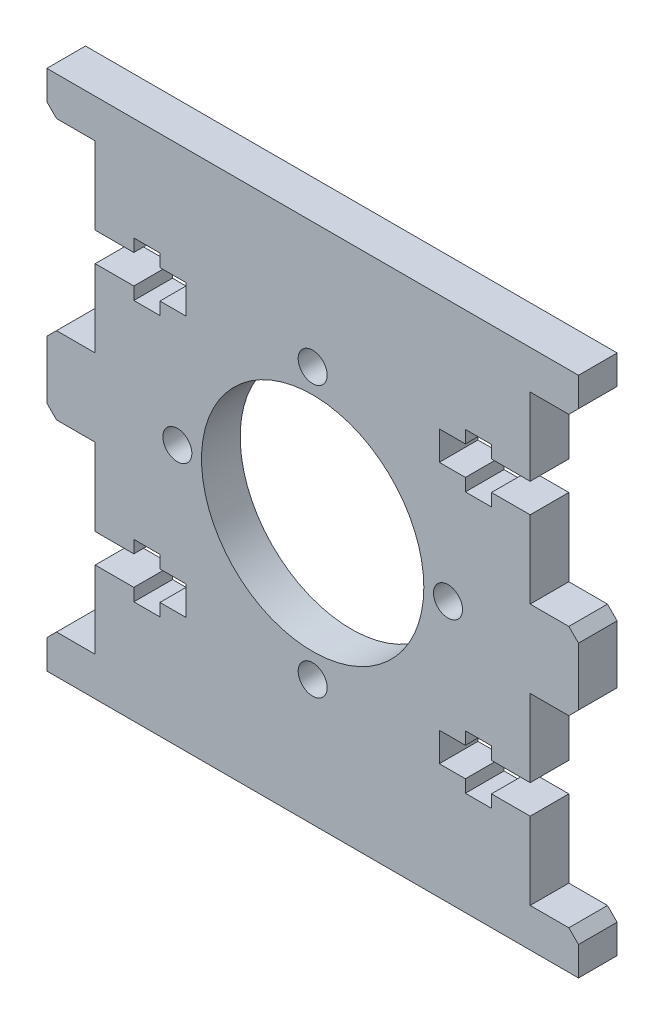
SolidWorks part; units mm, degrees
ref_plane "前视基准面" through (0, 0, 0) normal (0, 0, 1) x (1, 0, 0)
ref_plane "上视基准面" through (0, 0, 0) normal (0, 1, 0) x (1, 0, 0)
ref_plane "右视基准面" through (0, 0, 0) normal (1, 0, 0) x (0, 0, -1)
sketch "草图1" plane through (0, 0, 0) normal (0, 0, 1) x (1, 0, 0)
  line L0 (-22.5, 0) -> (-24.9483, 0) construction
  line L1 (22.5, -27) -> (-22.5, -27)
  line L3 (22.5, 27) -> (-22.5, 27)
  line L4 (-22.5, -27) -> (-22.5, 27) construction
  line L5 (22.5, -27) -> (-22.5, 27) construction
  line L6 (22.5, 27) -> (-22.5, -27) construction
  line L7 (-22.5, 4) -> (-27.5, 4)
  line L8 (-27.5, 4) -> (-27.5, -4)
  line L9 (-27.5, -4) -> (-22.5, -4)
  line L10 (-22.5, 15) -> (-18.5, 15)
  line L11 (-18.5, 15) -> (-18.5, 16.3)
  line L12 (-18.5, 16.3) -> (-15.8, 16.3)
  line L13 (-15.8, 16.3) -> (-15.8, 15)
  line L14 (-15.8, 15) -> (-13.1, 15)
  line L15 (-13.1, 15) -> (-13.1, 12)
  line L16 (-13.1, 12) -> (-15.8, 12)
  line L17 (-15.8, 12) -> (-15.8, 10.7)
  line L18 (-15.8, 10.7) -> (-18.5, 10.7)
  line L19 (-18.5, 10.7) -> (-18.5, 12)
  line L20 (-18.5, 12) -> (-22.5, 12)
  line L21 (-18.5, -12) -> (-22.5, -12)
  line L22 (-18.5, -10.7) -> (-18.5, -12)
  line L23 (-15.8, -10.7) -> (-18.5, -10.7)
  line L24 (-15.8, -12) -> (-15.8, -10.7)
  line L25 (-13.1, -12) -> (-15.8, -12)
  line L26 (-13.1, -15) -> (-13.1, -12)
  line L27 (-15.8, -15) -> (-13.1, -15)
  line L28 (-15.8, -16.3) -> (-15.8, -15)
  line L29 (-18.5, -16.3) -> (-15.8, -16.3)
  line L30 (-18.5, -15) -> (-18.5, -16.3)
  line L31 (-22.5, -15) -> (-18.5, -15)
  line L32 (-22.5, -23) -> (-27.5, -23)
  line L33 (-27.5, -23) -> (-27.5, -27)
  line L34 (-27.5, -27) -> (-22.5, -27)
  line L35 (-27.5, 23) -> (-27.5, 27)
  line L36 (-22.5, 23) -> (-27.5, 23)
  line L37 (-27.5, 27) -> (-22.5, 27)
  line L38 (0, 0) -> (0, -4) construction
  line L39 (22.5, -27) -> (22.5, 27) construction
  line L40 (22.5, 0) -> (24.9483, 0) construction
  line L41 (27.5, 27) -> (22.5, 27)
  line L42 (22.5, 23) -> (27.5, 23)
  line L43 (27.5, 23) -> (27.5, 27)
  line L44 (27.5, -27) -> (22.5, -27)
  line L45 (27.5, -23) -> (27.5, -27)
  line L46 (22.5, -23) -> (27.5, -23)
  line L47 (22.5, -15) -> (18.5, -15)
  line L48 (18.5, -15) -> (18.5, -16.3)
  line L49 (18.5, -16.3) -> (15.8, -16.3)
  line L50 (15.8, -16.3) -> (15.8, -15)
  line L51 (15.8, -15) -> (13.1, -15)
  line L52 (13.1, -15) -> (13.1, -12)
  line L53 (13.1, -12) -> (15.8, -12)
  line L54 (15.8, -12) -> (15.8, -10.7)
  line L55 (15.8, -10.7) -> (18.5, -10.7)
  line L56 (18.5, -10.7) -> (18.5, -12)
  line L57 (18.5, -12) -> (22.5, -12)
  line L58 (18.5, 12) -> (22.5, 12)
  line L59 (18.5, 10.7) -> (18.5, 12)
  line L60 (15.8, 10.7) -> (18.5, 10.7)
  line L61 (15.8, 12) -> (15.8, 10.7)
  line L62 (13.1, 12) -> (15.8, 12)
  line L63 (13.1, 15) -> (13.1, 12)
  line L64 (15.8, 15) -> (13.1, 15)
  line L65 (15.8, 16.3) -> (15.8, 15)
  line L66 (18.5, 16.3) -> (15.8, 16.3)
  line L67 (18.5, 15) -> (18.5, 16.3)
  line L68 (22.5, 15) -> (18.5, 15)
  line L69 (27.5, -4) -> (22.5, -4)
  line L70 (27.5, 4) -> (27.5, -4)
  line L71 (22.5, 4) -> (27.5, 4)
  line L72 (-22.5, 23) -> (-22.5, 15)
  line L73 (-22.5, 12) -> (-22.5, 4)
  line L74 (-22.5, -4) -> (-22.5, -12)
  line L75 (-22.5, -15) -> (-22.5, -23)
  line L76 (22.5, -23) -> (22.5, -15)
  line L77 (22.5, -12) -> (22.5, -4)
  line L78 (22.5, 4) -> (22.5, 12)
  line L79 (22.5, 23) -> (22.5, 15)
  circle A0 centre (0, 0) radius 14 construction
  circle A1 centre (14, 0) radius 1.5
  circle A5 centre (0, 0) radius 11.5
  circle A6 centre (0, -14) radius 1.5
  circle A7 centre (-14, 0) radius 1.5
  circle A8 centre (0, 14) radius 1.5
  point P35 (-17.15, 10.7)
  point P48 (-21.5, -15)
  point P91 (21.5, -15)
  dimension "D2" = 23
  dimension "D12" = 3
  dimension "D17" = 28
  dimension "D3" = 45
  dimension "D4" = 54
  dimension "D5" = 8
  dimension "D6" = 5
  dimension "D7" = 4
  dimension "D8" = 8
  dimension "D9" = 2.7
  dimension "D10" = 4
  dimension "D11" = 3
  dimension "D13" = 5.6
  dimension "D14" = 4
  dimension "D15" = 5
  dimension "D16" = 8
  dimension "D18" = 4
extrude "凸台-拉伸1" add sketch "草图1" along normal blind 4
sketch "草图2" plane through (-22.5, 0, 0) normal (-1, 0, 0) x (0, 0, 1)
  line L0 (2, 15) -> (2, 12) construction
  line L1 (4, 15) -> (0, 15) construction
  line L2 (4, 12) -> (0, 12) construction
  line L3 (-0.15, 27.15) -> (4.15, 27.15) construction
  line L4 (4.15, -4.15) -> (-0.15, -4.15)
  line L5 (4.15, -4.15) -> (4.15, 4.15)
  line L6 (4.15, 4.15) -> (-0.15, 4.15)
  line L7 (-0.15, -4.15) -> (-0.15, 4.15)
  line L8 (4.15, -4.15) -> (-0.15, 4.15) construction
  line L9 (4.15, 4.15) -> (-0.15, -4.15) construction
  line L18 (4.15, 27.15) -> (4.15, 22.85)
  line L19 (-0.15, 22.85) -> (4.15, 22.85)
  line L20 (-0.15, 27.15) -> (-0.15, 22.85)
  line L21 (2, 0) -> (2.8697, 0) construction
  line L22 (-0.15, -27.15) -> (4.15, -27.15) construction
  line L23 (2, -15) -> (2, -12) construction
  line L24 (-0.15, -27.15) -> (-0.15, -22.85)
  line L25 (-0.15, -22.85) -> (4.15, -22.85)
  line L26 (4.15, -27.15) -> (4.15, -22.85)
  line L27 (4.15, -27.15) -> (8, -27.15)
  line L28 (8, -27.15) -> (8, 27.15)
  line L29 (8, 27.15) -> (4.15, 27.15)
  line L30 (-0.15, -27.15) -> (-64.002, -27.15)
  line L31 (-64.002, -27.15) -> (-64.002, 27.15)
  line L32 (-64.002, 27.15) -> (-0.15, 27.15)
  circle A0 centre (2, 13.5) radius 1.5
  circle A1 centre (2, -13.5) radius 1.5
  point P8 (2, 0)
  dimension "D1" = 8.3
  dimension "D2" = 4.3
sketch "草图3" plane through (22.5, 0, 0) normal (1, 0, 0) x (0, 0, -1)
  line L0 (-2, 12) -> (-2, 15)
  line L1 (-4, 12) -> (0, 12) construction
  line L2 (-4, 15) -> (0, 15) construction
  circle A0 centre (-2, 13.5) radius 1.5
sketch "草图4" plane through (0, 0, 0) normal (0, 0, -1) x (-1, 0, 0)
  line L0 (-26.5, 4) -> (-27.5, 3)
  line L1 (-27.5, 4) -> (-22.5, 4) construction
  line L2 (-27.5, -4) -> (-27.5, 4) construction
  line L3 (-27.5, 3) -> (-27.5, 4)
  line L4 (-27.5, 4) -> (-26.5, 4)
  line L5 (-27.5, -3) -> (-26.5, -4)
  line L6 (-22.5, -4) -> (-27.5, -4) construction
  line L7 (-26.5, -4) -> (-27.5, -4)
  line L8 (-27.5, -4) -> (-27.5, -3)
  line L9 (-27.5, -23) -> (-26.5, -23)
  line L10 (-27.5, -23) -> (-22.5, -23) construction
  line L11 (-26.5, -23) -> (-27.5, -24)
  line L12 (-27.5, -27) -> (-27.5, -23) construction
  line L13 (-27.5, -24) -> (-27.5, -23)
  line L14 (-27.5, 24) -> (-26.5, 23)
  line L15 (-27.5, 23) -> (-27.5, 27) construction
  line L16 (-22.5, 23) -> (-27.5, 23) construction
  line L17 (-26.5, 23) -> (-27.5, 23)
  line L18 (-27.5, 23) -> (-27.5, 24)
  line L19 (0, 0) -> (0, -6.1744) construction
  line L20 (27.5, 23) -> (27.5, 24)
  line L21 (26.5, 23) -> (27.5, 23)
  line L22 (27.5, 24) -> (26.5, 23)
  line L23 (27.5, -24) -> (27.5, -23)
  line L24 (26.5, -23) -> (27.5, -24)
  line L25 (27.5, -23) -> (26.5, -23)
  line L26 (27.5, -4) -> (27.5, -3)
  line L27 (26.5, -4) -> (27.5, -4)
  line L28 (27.5, -3) -> (26.5, -4)
  line L29 (27.5, 4) -> (26.5, 4)
  line L30 (27.5, 3) -> (27.5, 4)
  line L31 (26.5, 4) -> (27.5, 3)
extrude "切除-拉伸1" cut sketch "草图4" against normal blind 4
